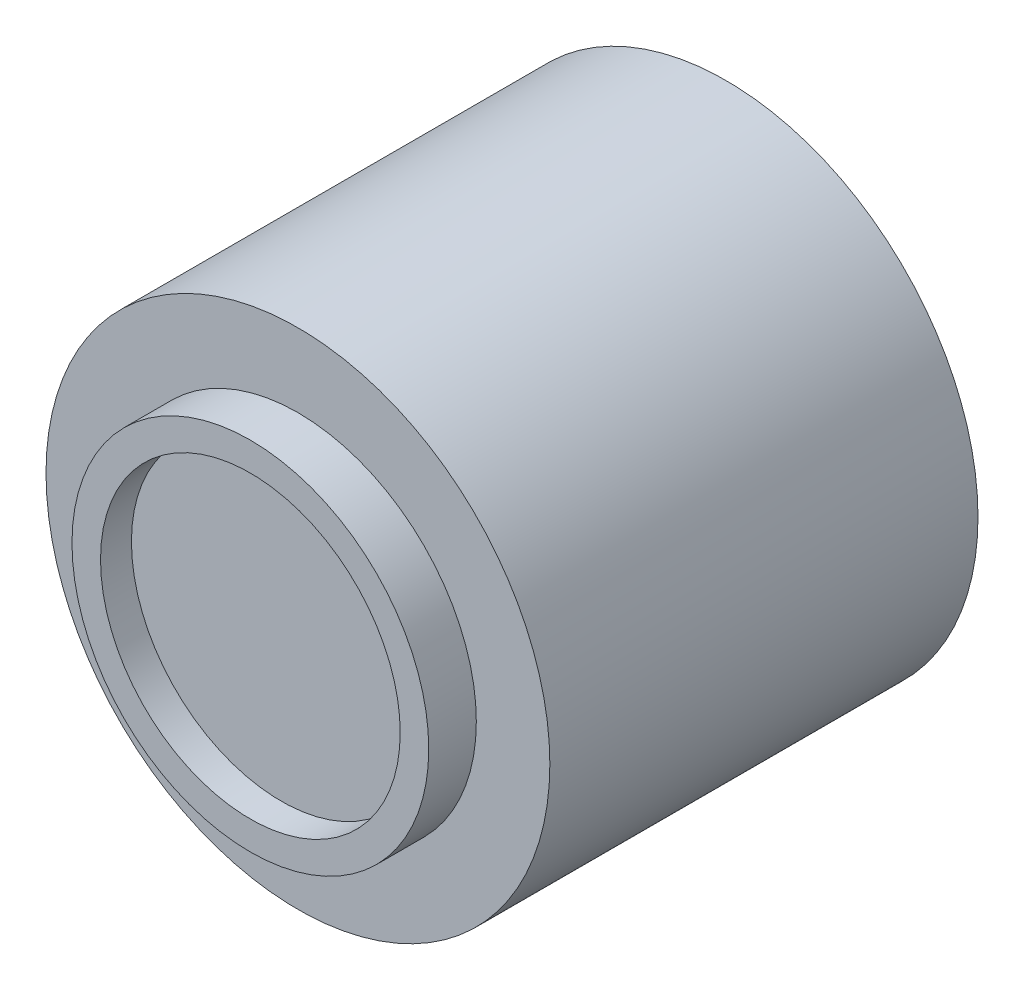
SolidWorks part; units mm, degrees
ref_plane "Front Plane" through (0, 0, 0) normal (0, 0, 1) x (1, 0, 0)
ref_plane "Top Plane" through (0, 0, 0) normal (0, 1, 0) x (1, 0, 0)
ref_plane "Right Plane" through (0, 0, 0) normal (1, 0, 0) x (0, 0, -1)
sketch "Sketch1" plane through (0, 0, 0) normal (0, 0, 1) x (1, 0, 0)
  circle A0 centre (0, 0) radius 37.5
  dimension "D1" = 75
extrude "Boss-Extrude1" add sketch "Sketch1" along normal blind 100
sketch "Sketch2" plane through (0, 0, 100) normal (0, 0, 1) x (1, 0, 0)
  circle A0 centre (0, 0) radius 31.5
  dimension "D1" = 63
extrude "Cut-Extrude1" cut sketch "Sketch2" against normal blind 6.5
sketch "Sketch3" plane through (0, 0, 0) normal (0, 0, -1) x (-1, 0, 0)
  circle A0 centre (0, 0) radius 52.9597
extrude "Boss-Extrude2" add sketch "Sketch3" against normal blind 90
